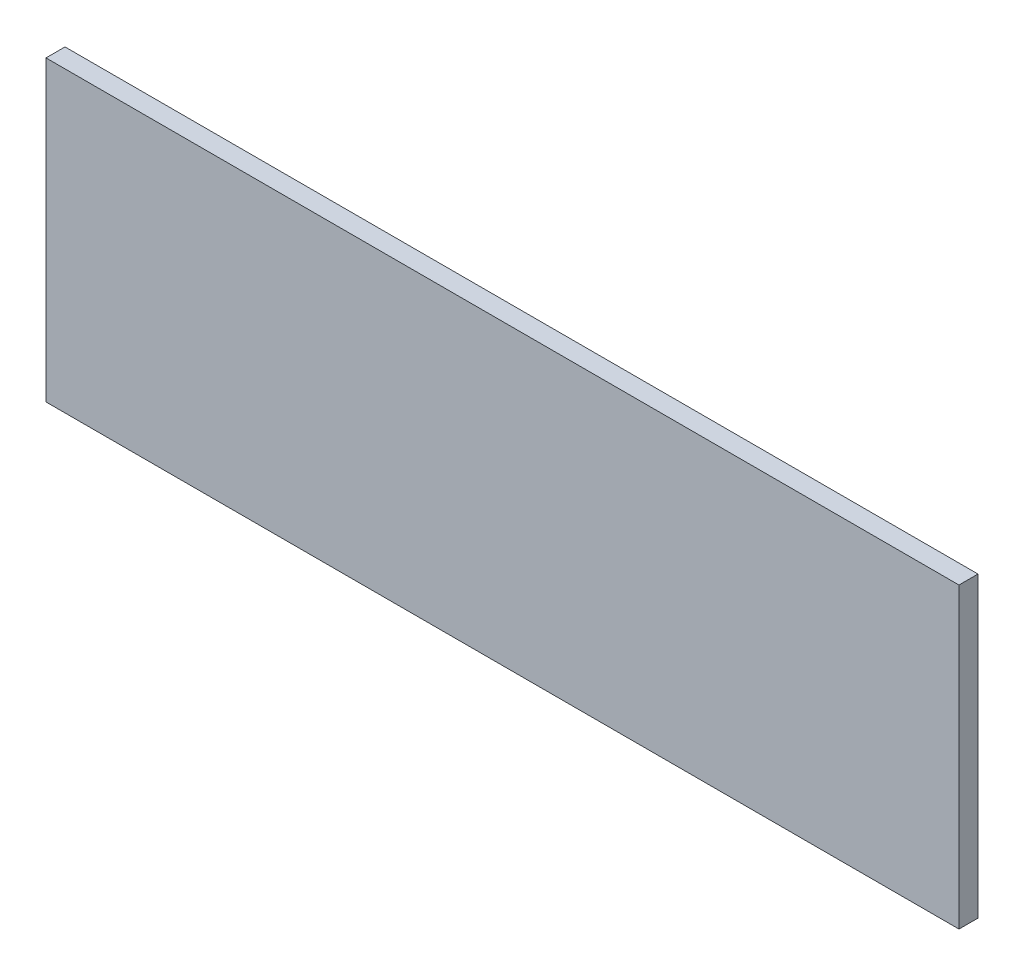
SolidWorks part; units mm, degrees
ref_plane "Front Plane" through (0, 0, 0) normal (0, 0, 1) x (1, 0, 0)
ref_plane "Top Plane" through (0, 0, 0) normal (0, 1, 0) x (1, 0, 0)
ref_plane "Right Plane" through (0, 0, 0) normal (1, 0, 0) x (0, 0, -1)
sketch "Sketch1" plane through (0, 0, 0) normal (0, 0, 1) x (1, 0, 0)
  line L0 (15.6443, 243.1814) -> (159.6443, 243.1814)
  line L1 (159.6443, 243.1814) -> (159.6443, 196.1814)
  line L2 (159.6443, 196.1814) -> (15.6443, 196.1814)
  line L3 (15.6443, 196.1814) -> (15.6443, 243.1814)
  dimension "D1" = 47
  dimension "D2" = 144
extrude "Boss-Extrude1" add sketch "Sketch1" along normal blind 3 contours L3 L0 L1 L2
